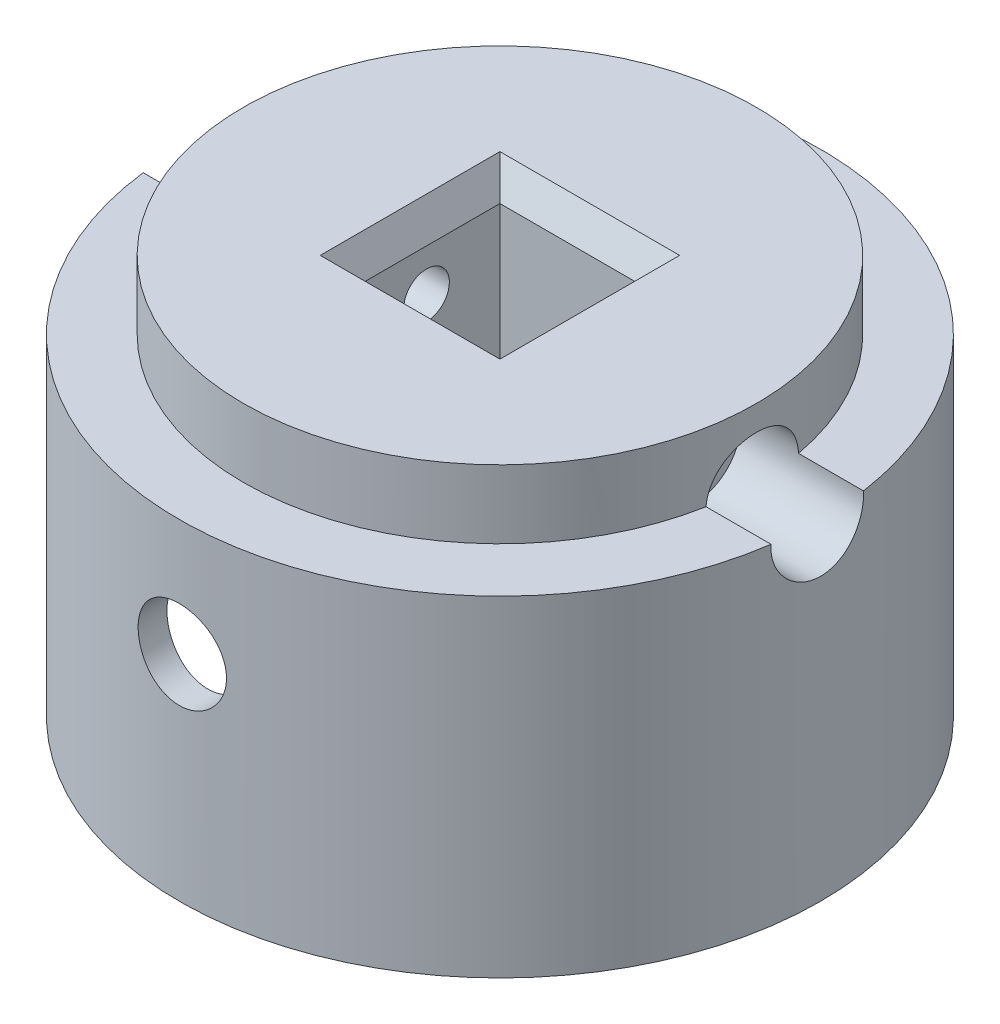
SolidWorks part; units mm, degrees
ref_plane "Спереди" through (0, 0, 0) normal (0, 0, 1) x (1, 0, 0)
ref_plane "Сверху" through (0, 0, 0) normal (0, 1, 0) x (1, 0, 0)
ref_plane "Справа" through (0, 0, 0) normal (1, 0, 0) x (0, 0, -1)
sketch "Sketch1" plane through (0, 0, 0) normal (0, 1, 0) x (1, 0, 0)
  circle A0 centre (0, 0) radius 22.5
  dimension "D1" = 45
extrude "Boss-Extrude1" add sketch "Sketch1" along normal blind 28
sketch "Sketch2" plane through (0, 0, 0) normal (0, -1, 0) x (1, 0, 0)
  line L1 (5.15, 5.15) -> (-5.15, 5.15)
  line L2 (5.15, 5.15) -> (5.15, -5.15)
  line L3 (5.15, -5.15) -> (-5.15, -5.15)
  line L4 (-5.15, 5.15) -> (-5.15, -5.15)
  line L5 (5.15, 5.15) -> (-5.15, -5.15) construction
  line L6 (5.15, -5.15) -> (-5.15, 5.15) construction
  point P0 (0, 0)
  dimension "D1" = 10.3
extrude "Cut-Extrude2" cut sketch "Sketch2" against normal through all
shell "Shell3" thickness 2
sketch "Sketch3" plane through (0, 0, 7.15) normal (0, 0, 1) x (1, 0, 0)
  line L0 (0, 26) -> (0, 0) construction
  line L1 (7.15, 26) -> (-7.15, 26) construction
  line L2 (7.15, 0) -> (-7.15, 0) construction
  line L3 (-22.5, 0) -> (22.5, 0) construction
  circle A0 centre (0, 15) radius 3.1
  dimension "D1" = 6.2
  dimension "D2" = 15
extrude "Cut-Extrude3" cut sketch "Sketch3" along normal through all
chamfer "Chamfer1" distance 2 angle 30 4 edges at (-5.15, 28, 0) (0, 28, 5.15) (5.15, 28, 0) (0, 28, -5.15)
sketch "Sketch18" plane through (0, 26, 0) normal (0, -1, 0) x (1, 0, 0)
  line L0 (0, 0) -> (-18.4253, -8.9866) construction
  line L1 (0, 0) -> (-17.385, 10.8633) construction
  line L2 (0, 0) -> (0, -20.5) construction
  line L3 (-15.7289, -7.6715) -> (-18.4253, -8.9866)
  line L4 (-14.8408, 9.2736) -> (-17.385, 10.8633)
  circle A0 centre (0, 0) radius 20.5 construction
  arc A1 (-18.4253, -8.9866) -> (-17.385, 10.8633) centre (0, 0) cw
  arc A2 (-14.8408, 9.2736) -> (-15.7289, -7.6715) centre (0, 0) ccw
  dimension "D1" = 64
  dimension "D2" = 58
  dimension "D3" = 3
extrude "Boss-Extrude8" add sketch "Sketch18" along normal offset from surface (23 mm away) 3 up to face at (0, 0, 20.5)
sketch "Sketch9" plane through (0, 0, 0) normal (0, -1, 0) x (1, 0, 0)
  line L0 (0, -7.15) -> (0, -20.5) construction
  line L2 (2.0571, -22.4058) -> (-16.5967, -15.1921)
  line L3 (-16.5967, -15.1921) -> (-17.6788, -17.9902)
  line L4 (-17.6788, -17.9902) -> (0.975, -25.2038)
  line L5 (0.975, -25.2038) -> (2.0571, -22.4058)
  line L6 (-7.15, -7.15) -> (7.15, -7.15) construction
  line L7 (2.0571, -22.4058) -> (0, -7.15) construction
  circle A0 centre (0, 0) radius 22.5 construction
  circle A1 centre (0, 0) radius 20.5 construction
  dimension "D1" = 20
  dimension "D2" = 3
  dimension "D3" = 7.679
extrude "Boss-Extrude4" add sketch "Sketch9" against normal blind 20
sketch "Sketch11" plane through (0, 0, 0) normal (0, -1, 0) x (1, 0, 0)
  line L0 (2.0571, -22.4058) -> (7.15, -7.15)
  line L1 (7.15, -7.15) -> (-7.15, -7.15)
  line L2 (-7.15, -7.15) -> (-16.5967, -15.1921)
  line L3 (-16.5967, -15.1921) -> (2.0571, -22.4058) construction
  line L4 (-3.78, -20.1485) -> (-10.7596, -17.4494) construction
  arc A0 (2.0571, -22.4058) -> (-16.5967, -15.1921) centre (0, 0) ccw construction
  arc A1 (2.0571, -22.4058) -> (-16.5967, -15.1921) centre (0, 0) cw
  arc A2 (2.0571, -22.4058) -> (-16.5967, -15.1921) centre (0, 0) ccw construction
  point P4 (-7.2698, -18.7989)
extrude "Boss-Extrude6" add sketch "Sketch11" against normal up to surface (26 mm away) up to face at (0, 26, 0)
sketch "Sketch12" plane through (0, 0, 0) normal (0, -1, 0) x (1, 0, 0)
  line L0 (-7.15, -7.15) -> (-15.0727, -13.8947) construction
  line L1 (2.7554, -20.314) -> (7.15, -7.15) construction
  line L2 (3.8359, -17.0772) -> (2.7554, -20.314)
  line L3 (-15.0727, -13.8947) -> (-12.7884, -11.95)
  arc A0 (2.7554, -20.314) -> (-15.0727, -13.8947) centre (0, 0) cw
  arc A1 (-12.7884, -11.95) -> (3.8359, -17.0772) centre (0, 0) ccw
  arc A2 (2.7554, -20.314) -> (-15.0727, -13.8947) centre (0, 0) ccw construction
  dimension "D1" = 3
extrude "Cut-Extrude5" cut sketch "Sketch12" against normal blind 10
sketch "Sketch13" plane through (-8.3519, 0, -21.597) normal (-0.3607, 0, -0.9327) x (-0.9327, 0, 0.3607)
  line L0 (0, 20) -> (0, 0) construction
  line L1 (10, 20) -> (-10, 20) construction
  line L2 (10, 0) -> (-10, 0) construction
  circle A0 centre (0, 10) radius 3.8
  dimension "D1" = 7.6
extrude "Cut-Extrude6" cut sketch "Sketch13" against normal blind 16
sketch "Sketch15" plane through (-8.3519, 0, -21.597) normal (-0.3607, 0, -0.9327) x (-0.9327, 0, 0.3607)
  line L0 (-10, 10) -> (10, 10) construction
  line L1 (-10, 20) -> (-10, 0) construction
  line L2 (10, 20) -> (10, 0) construction
  line L4 (5, 11.5) -> (-5, 11.5)
  line L5 (5, 11.5) -> (5, 8.5)
  line L6 (5, 8.5) -> (-5, 8.5)
  line L7 (-5, 11.5) -> (-5, 8.5)
  line L8 (5, 11.5) -> (-5, 8.5) construction
  line L9 (5, 8.5) -> (-5, 11.5) construction
  point P6 (0, 10)
  dimension "D1" = 10
  dimension "D2" = 3
extrude "Cut-Extrude8" cut sketch "Sketch15" against normal blind 16
sketch "Sketch17" plane through (0, 0, 0) normal (0, -1, 0) x (1, 0, 0)
  line L0 (7.15, 7.15) -> (7.15, -7.15)
  line L1 (7.15, -7.15) -> (3.8359, -17.0772)
  line L2 (7.15, 7.15) -> (-7.15, 7.15)
  line L3 (-7.15, 7.15) -> (-7.15, -7.15)
  line L4 (-7.15, -7.15) -> (-12.7884, -11.95)
  arc A0 (3.8359, -17.0772) -> (-12.7884, -11.95) centre (0, 0) cw
  arc A1 (-12.7884, -11.95) -> (3.8359, -17.0772) centre (0, 0) ccw construction
extrude "Cut-Extrude9" cut sketch "Sketch17" against normal blind 2
sketch "Sketch20" plane through (0, 26, 0) normal (0, -1, 0) x (1, 0, 0)
  line L0 (2.7554, -20.314) -> (7.15, -7.15)
  line L1 (7.15, -7.15) -> (7.15, 7.15)
  line L2 (7.15, 7.15) -> (-7.15, 7.15)
  line L3 (-7.15, 7.15) -> (-7.15, -7.15)
  line L4 (-7.15, -7.15) -> (-15.0727, -13.8947)
  arc A0 (2.7554, -20.314) -> (-15.0727, -13.8947) centre (0, 0) ccw
  arc A1 (2.7554, -20.314) -> (-17.385, 10.8633) centre (0, 0) ccw construction
extrude "Boss-Extrude10" add sketch "Sketch20" along normal blind 7
sketch "Sketch21" plane through (0, 28, 0) normal (0, 1, 0) x (1, 0, 0)
  circle A0 centre (0, 0) radius 18
  dimension "D1" = 36
extrude "Cut-Extrude11" cut sketch "Sketch21" against normal blind 4.8 flip side to cut
sketch "Sketch22" plane through (5.15, 0, 0) normal (-1, 0, 0) x (0, 0, 1)
  line L0 (0, 26) -> (0, 2) construction
  line L1 (5.15, 26) -> (-5.15, 26) construction
  line L2 (-5.15, 2) -> (5.15, 2) construction
  line L3 (-6.3047, 28) -> (6.3047, 28) construction
  circle A0 centre (0, 23) radius 1.6
  point P10 (0, 28)
  dimension "D1" = 3.2
  dimension "D2" = 5
extrude "Cut-Extrude12" cut sketch "Sketch22" against normal through all both and the other way through all
sketch "Sketch24" plane through (5.15, 0, 0) normal (-1, 0, 0) x (0, 0, 1)
  circle A0 centre (0, 23) radius 3.25
  dimension "D1" = 6.5
extrude "Cut-Extrude13" cut sketch "Sketch24" against normal through all from offset 8.5 offset against normal yes
sketch "Sketch25" plane through (-5.15, 0, 0) normal (1, 0, 0) x (0, 0, -1)
  line L0 (-5.15, 26) -> (-5.15, 2) construction
  line L1 (0, 19.8936) -> (2.6903, 21.4468)
  line L2 (2.6903, 21.4468) -> (2.6903, 24.5532)
  line L3 (2.6903, 24.5532) -> (0, 26.1064)
  line L4 (0, 26.1064) -> (-2.6903, 24.5532)
  line L5 (-2.6903, 24.5532) -> (-2.6903, 21.4468)
  line L6 (-2.6903, 21.4468) -> (0, 19.8936)
  circle A0 centre (0, 23) radius 3.1064 construction
extrude "Cut-Extrude14" cut sketch "Sketch25" against normal through all from offset 8.5
